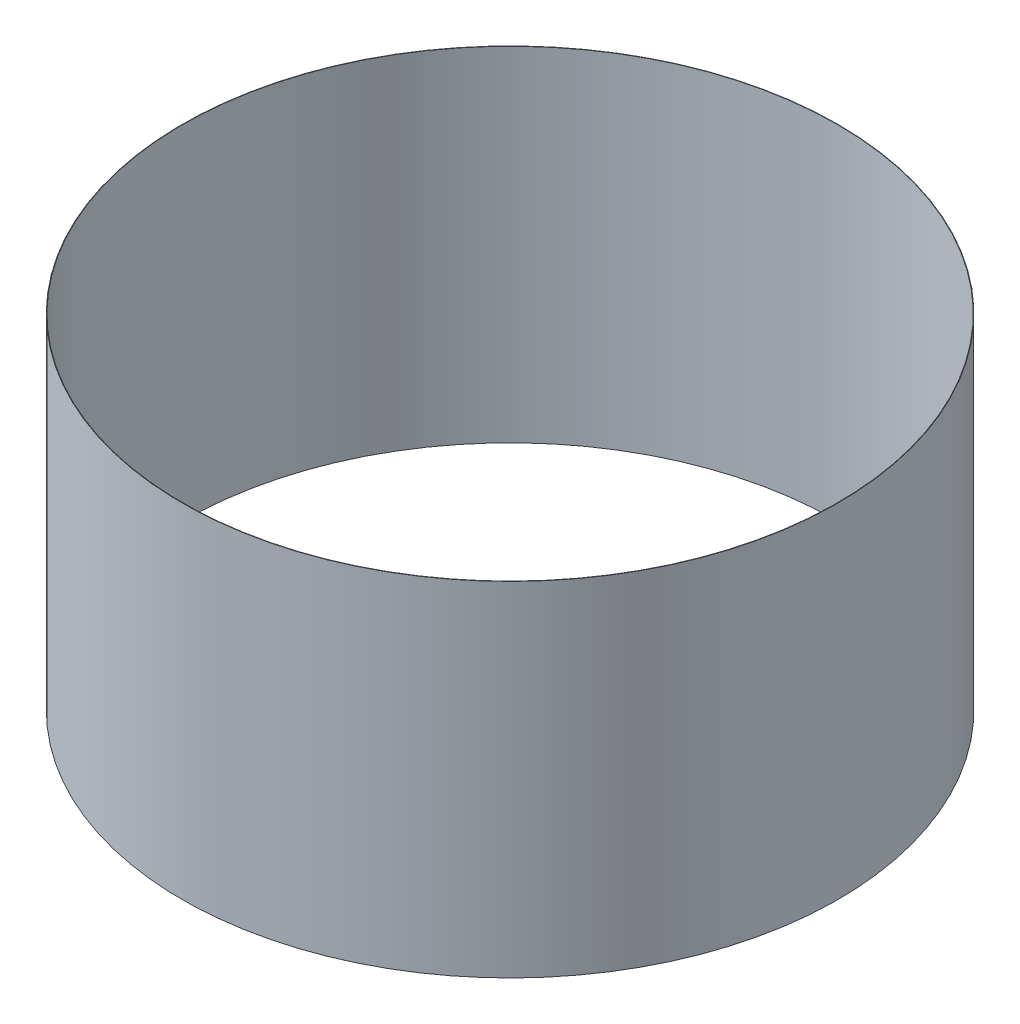
SolidWorks part; units mm, degrees
material "Custom Plastic"
ref_plane "Front Plane" through (0, 0, 0) normal (0, 0, 1) x (1, 0, 0)
ref_plane "Top Plane" through (0, 0, 0) normal (0, 1, 0) x (1, 0, 0)
ref_plane "Right Plane" through (0, 0, 0) normal (1, 0, 0) x (0, 0, -1)
sketch "Sketch1" plane through (0, 0, 0) normal (0, 1, 0) x (1, 0, 0)
  circle A0 centre (0, 0) radius 195.5
  dimension "D1" = 391
extrude "Extrude-Thin1" add sketch "Sketch1" along normal blind 205 thin
